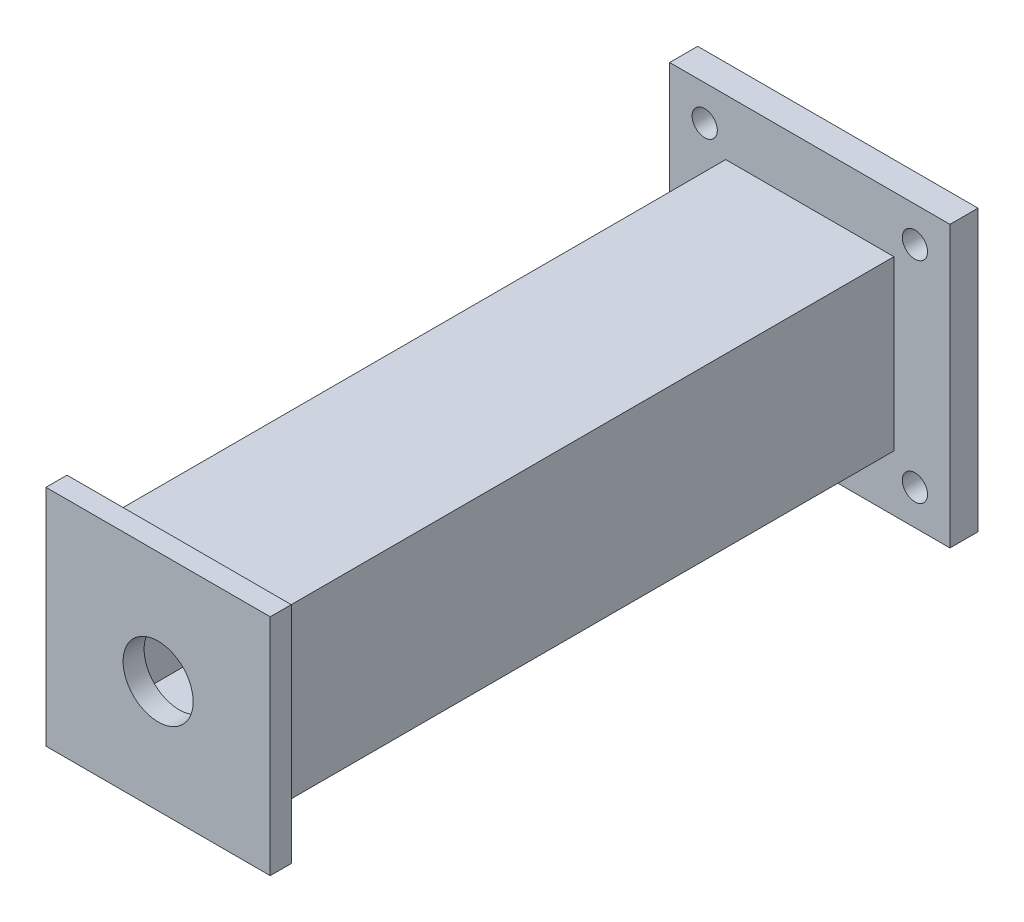
SolidWorks part; units mm, degrees
ref_plane "前视基准面" through (0, 0, 0) normal (0, 0, 1) x (1, 0, 0)
ref_plane "上视基准面" through (0, 0, 0) normal (0, 1, 0) x (1, 0, 0)
ref_plane "右视基准面" through (0, 0, 0) normal (1, 0, 0) x (0, 0, -1)
other "Configuration Table"
sketch "草图8" plane through (0, 0, 0) normal (0, 0, 1) x (1, 0, 0)
  line L1 (-60, 60) -> (60, 60)
  line L2 (-60, 60) -> (-60, -60)
  line L3 (-60, -60) -> (60, -60)
  line L4 (60, 60) -> (60, -60)
  line L5 (-50, 50) -> (50, 50)
  line L6 (-50, 50) -> (-50, -50)
  line L7 (-50, -50) -> (50, -50)
  line L8 (50, 50) -> (50, -50)
extrude "凸台-拉伸1" add sketch "草图8" along normal mid plane 450
sketch "草图9" plane through (0, 0, 225) normal (0, 0, 1) x (1, 0, 0)
  line L1 (-80, 80) -> (80, 80)
  line L2 (-80, 80) -> (-80, -80)
  line L3 (-80, -80) -> (80, -80)
  line L4 (80, 80) -> (80, -80)
  circle A0 centre (0, 0) radius 25
extrude "凸台-拉伸2" add sketch "草图9" along normal blind 15
sketch "草图10" plane through (0, 0, -225) normal (0, 0, -1) x (-1, 0, 0)
  line L1 (-100, 100) -> (100, 100)
  line L2 (-100, 100) -> (-100, -100)
  line L3 (-100, -100) -> (100, -100)
  line L4 (100, 100) -> (100, -100)
  circle A0 centre (75, 75) radius 9
  circle A1 centre (-75, 75) radius 9
  circle A2 centre (75, -75) radius 9
  circle A3 centre (-75, -75) radius 9
extrude "凸台-拉伸3" add sketch "草图10" along normal blind 20
